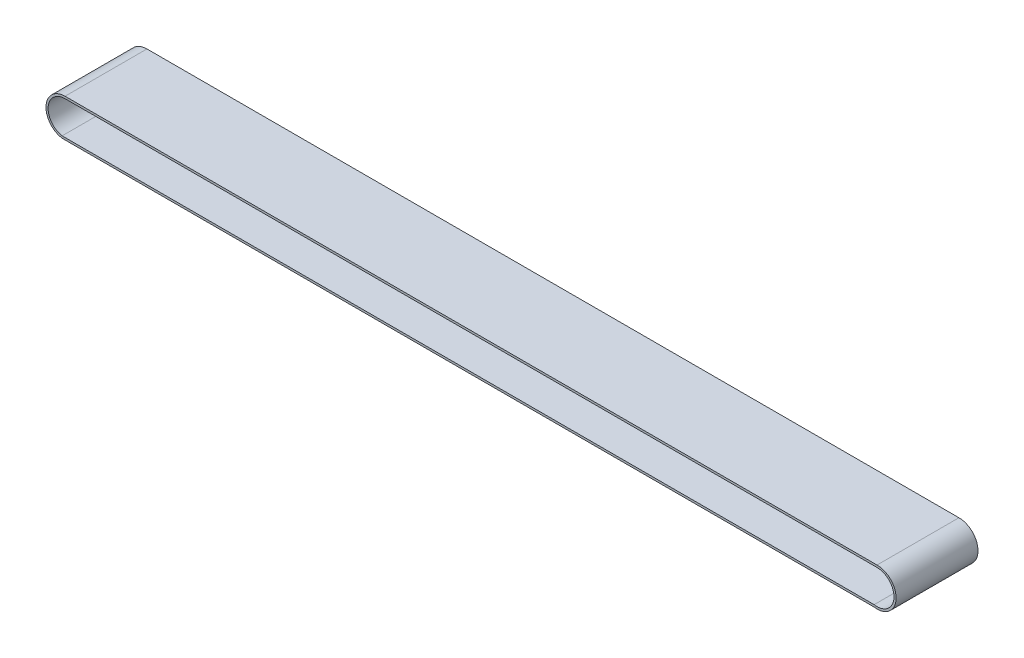
SolidWorks part; units mm, degrees
ref_plane "Alzado" through (0, 0, 0) normal (0, 0, 1) x (1, 0, 0)
ref_plane "Planta" through (0, 0, 0) normal (0, 1, 0) x (1, 0, 0)
ref_plane "Vista lateral" through (0, 0, 0) normal (1, 0, 0) x (0, 0, -1)
sketch "Croquis1" plane through (0, 0, 0) normal (0, 0, 1) x (1, 0, 0)
  line L1 (-288.5929, -13.4109) -> (286.4071, -13.4109)
  line L3 (-286.4071, 13.4109) -> (288.5929, 13.4109)
  line L5 (-288.5929, -13.4109) -> (288.5929, 13.4109) construction
  line L6 (-286.4071, 13.4109) -> (286.4071, -13.4109) construction
  arc A0 (286.4071, -13.4109) -> (288.5929, 13.4109) centre (288.5929, -0.0891) ccw
  arc A1 (-286.4071, 13.4109) -> (-288.5929, -13.4109) centre (-286.4071, -0.0891) ccw
  point P0 (0, 0)
  dimension "D2" = 13.5
  dimension "D1" = 575
  dimension "D3" = 26.8219
extrude "Saliente-Extruir1" add sketch "Croquis1" along normal mid plane 58
shell "Vaciado3" thickness 1.5
